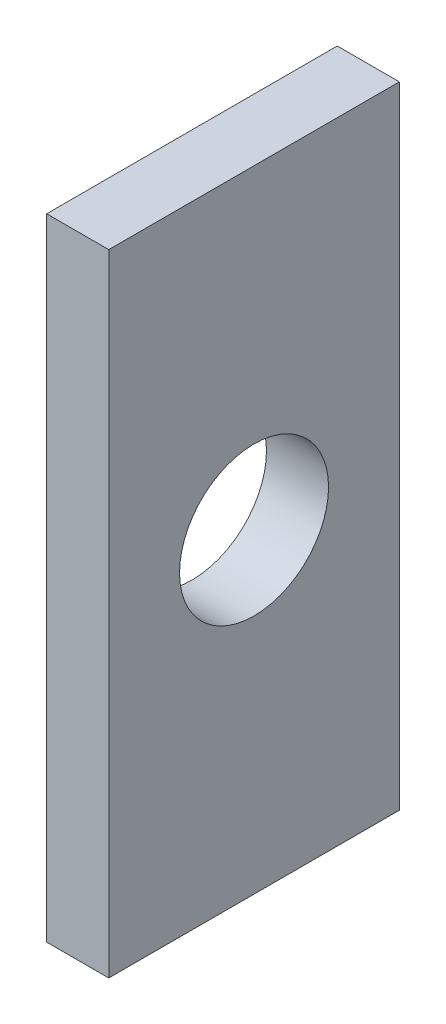
SolidWorks part; units mm, degrees
material "Custom Plastic"
ref_plane "X-Y Datum" through (0, 0, 0) normal (0, 0, 1) x (1, 0, 0)
ref_plane "X-Z Datum" through (0, 0, 0) normal (0, 1, 0) x (1, 0, 0)
ref_plane "Y-Z Datum" through (0, 0, 0) normal (1, 0, 0) x (0, 0, -1)
sketch "Sketch1" plane through (0, 0, 0) normal (1, 0, 0) x (0, 0, -1)
  line L4 (-261.0825, -37.9961) -> (-261.0825, -12.5961)
  line L5 (-272.7825, -37.9961) -> (-261.0825, -37.9961)
  line L6 (-272.7825, -12.5961) -> (-272.7825, -37.9961)
  line L7 (-261.0825, -12.5961) -> (-272.7825, -12.5961)
  line L8 (-261.0825, -37.9961) -> (-261.0825, -12.5961)
  line L9 (-272.7825, -37.9961) -> (-261.0825, -37.9961)
  line L10 (-272.7825, -12.5961) -> (-272.7825, -37.9961)
  line L11 (-261.0825, -12.5961) -> (-272.7825, -12.5961)
  circle A0 centre (-266.9325, -25.2961) radius 3
  point P2 (-266.9325, -25.2961)
  dimension "D2" = 6
  dimension "D1" = 0
extrude "Boss-Extrude1" add sketch "Sketch1" along normal blind 2.5
